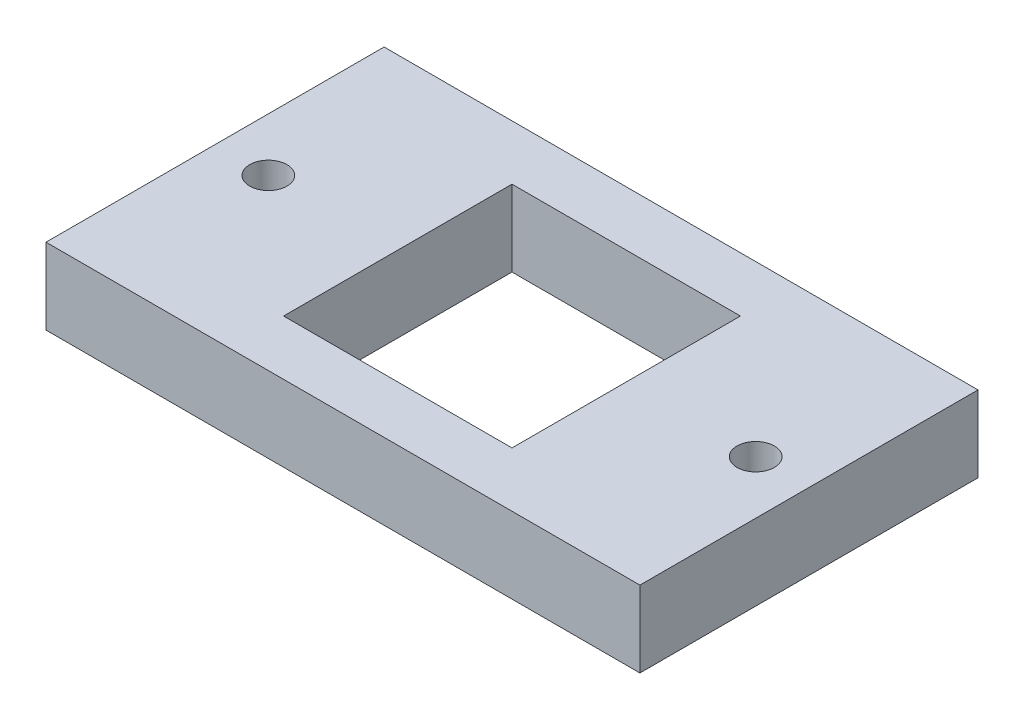
SolidWorks part; units mm, degrees
ref_plane "前视基准面" through (0, 0, 0) normal (0, 0, 1) x (1, 0, 0)
ref_plane "上视基准面" through (0, 0, 0) normal (0, 1, 0) x (1, 0, 0)
ref_plane "右视基准面" through (0, 0, 0) normal (1, 0, 0) x (0, 0, -1)
sketch "草图1" plane through (0, 0, 0) normal (0, 1, 0) x (1, 0, 0)
  line L1 (-46.197, 29.6557) -> (-26.197, 29.6557) construction
  line L2 (-46.197, 29.6557) -> (-46.197, 9.6557) construction
  line L3 (-46.197, 9.6557) -> (-26.197, 9.6557) construction
  line L4 (-26.197, 29.6557) -> (-26.197, 9.6557) construction
  line L5 (-54.949, 19.6557) -> (-13.399, 19.6557) construction
  line L6 (-55.697, 30.7557) -> (-16.697, 30.7557)
  line L7 (-55.697, 30.7557) -> (-55.697, 8.5557)
  line L8 (-55.697, 8.5557) -> (-16.697, 8.5557)
  line L9 (-16.697, 30.7557) -> (-16.697, 8.5557)
  line L30 (-43.697, 27.1557) -> (-28.697, 27.1557)
  line L31 (-43.697, 27.1557) -> (-43.697, 12.1557)
  line L32 (-43.697, 12.1557) -> (-28.697, 12.1557)
  line L33 (-28.697, 27.1557) -> (-28.697, 12.1557)
  line L37 (-46.297, 29.7557) -> (-26.097, 29.7557) construction
  line L38 (-26.097, 29.7557) -> (-26.097, 9.5557) construction
  line L39 (-46.297, 9.5557) -> (-26.097, 9.5557) construction
  line L40 (-46.297, 29.7557) -> (-46.297, 9.5557) construction
  line L50 (-36.197, 33.8677) -> (-36.197, 5.7357) construction
  circle A2 centre (-52.197, 19.6557) radius 1.225
  circle A3 centre (-20.197, 19.6557) radius 1.225
  point P21 (-28.697, 19.6557)
  point P26 (-36.197, 27.1557)
  dimension "D10" = 2.45
  dimension "D1" = 20
  dimension "D2" = 1
  dimension "D3" = 1
  dimension "D4" = 15
  dimension "D5" = 2.5
  dimension "D6" = 2.5
  dimension "D9" = 6
  dimension "D11" = 6
  dimension "D7" = 3.5
  dimension "D14" = 3.5
  dimension "D8" = 0.1
extrude "凸台-拉伸1" add sketch "草图1" along normal blind 5
